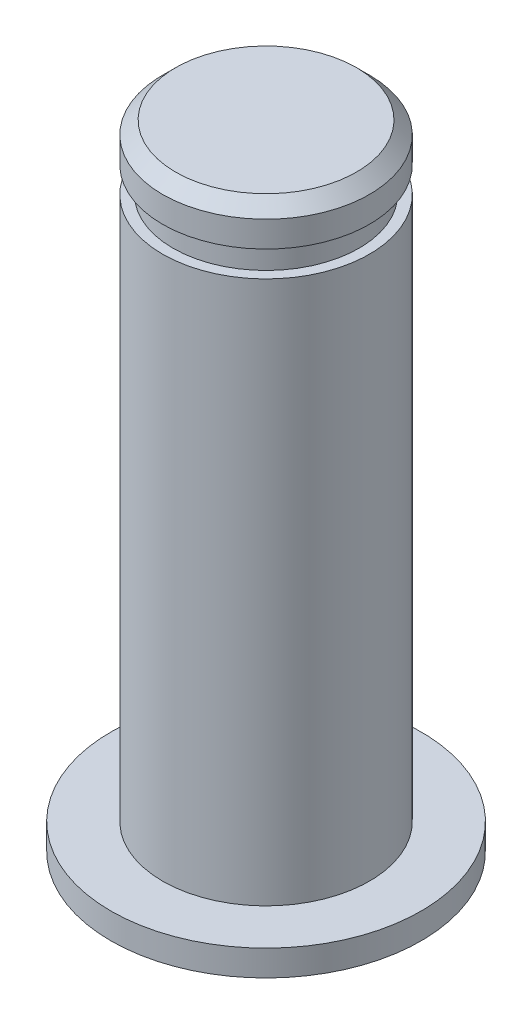
SolidWorks part; units mm, degrees
ref_plane "Спереди" through (0, 0, 0) normal (0, 0, 1) x (1, 0, 0)
ref_plane "Сверху" through (0, 0, 0) normal (0, 1, 0) x (1, 0, 0)
ref_plane "Справа" through (0, 0, 0) normal (1, 0, 0) x (0, 0, -1)
sketch "Эскиз1" plane through (0, 0, 0) normal (0, 0, 1) x (1, 0, 0)
  line L0 (-4, 24.5) -> (0, 24.5)
  line L1 (0, 24.5) -> (0, 0)
  line L2 (0, 0) -> (-6, 0)
  line L3 (-6, 0) -> (-6, 1)
  line L4 (-6, 1) -> (-4, 1)
  line L5 (-4, 1) -> (-4, 22)
  line L6 (-4, 22) -> (-3.6, 22)
  line L7 (-3.6, 22) -> (-3.6, 23)
  line L8 (-3.6, 23) -> (-4, 23)
  line L9 (-4, 23) -> (-4, 24.5)
  line L10 (0, 0) -> (0, -50000) construction
  line L12 (4, 22) -> (-4, 22) construction
  line L13 (4, 22) -> (-4, 22) construction
  line L14 (4, 22) -> (-4, 22) construction
  line L16 (3.6, 23) -> (-3.6, 23) construction
  line L18 (3.6, 23) -> (-3.6, 23) construction
  dimension "D1" = 1.5
  dimension "D2" = 2
  dimension "D3" = 1
revolve "Повернуть1" add sketch "Эскиз1" angle 360 about L10
chamfer "Фаска1" distance 0.5 angle 45 1 edges at (0, 24.5, 4)
